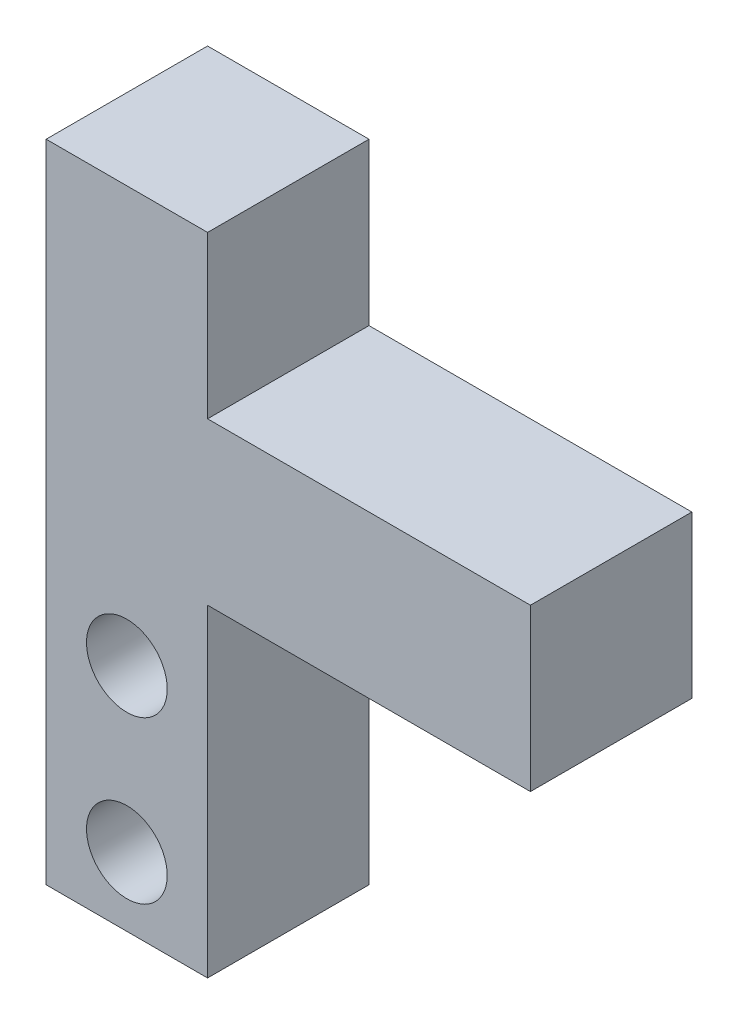
SolidWorks part; units mm, degrees
ref_plane "Plan de face" through (0, 0, 0) normal (0, 0, 1) x (1, 0, 0)
ref_plane "Plan de dessus" through (0, 0, 0) normal (0, 1, 0) x (1, 0, 0)
ref_plane "Plan de droite" through (0, 0, 0) normal (1, 0, 0) x (0, 0, -1)
sketch "Esquisse1" plane through (0, 0, 0) normal (0, 0, 1) x (1, 0, 0)
  line L0 (5, 10) -> (5, 20)
  line L1 (-5, -20) -> (5, -20)
  line L2 (-5, -20) -> (-5, 20)
  line L3 (-5, 20) -> (5, 20)
  line L4 (5, -20) -> (5, 0)
  line L5 (-5, -20) -> (5, 20) construction
  line L6 (-5, 20) -> (5, -20) construction
  line L7 (5, 0) -> (25, 0)
  line L9 (5, 10) -> (25, 10)
  line L10 (25, 0) -> (25, 10)
  circle A0 centre (0, -5.7492) radius 2.5
  circle A1 centre (0, -15.7492) radius 2.5
  point P0 (0, 0)
  dimension "D5" = 5
  dimension "D6" = 5
  dimension "D1" = 40
  dimension "D2" = 10
  dimension "D3" = 10
  dimension "D4" = 20
  dimension "D7" = 10
extrude "Boss.-Extru.1" add sketch "Esquisse1" along normal blind 10
